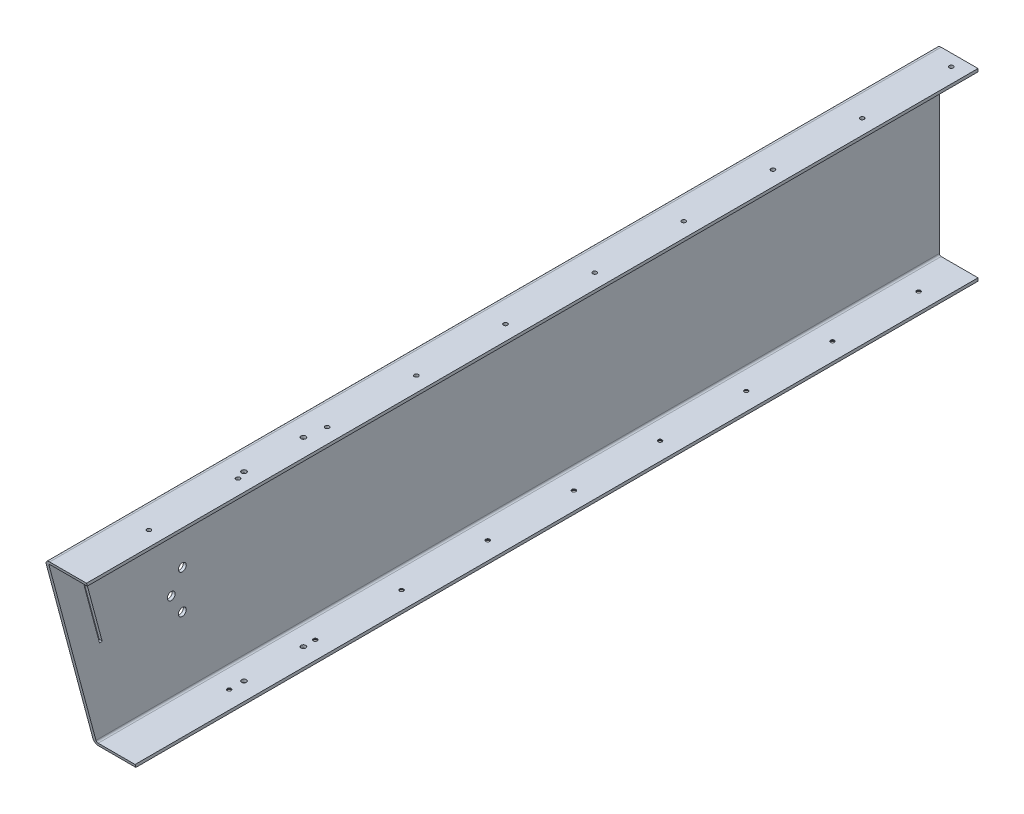
SolidWorks part; units mm, degrees
material "AISI 304"
ref_plane "Спереди" through (0, 0, 0) normal (0, 0, 1) x (1, 0, 0)
ref_plane "Сверху" through (0, 0, 0) normal (0, 1, 0) x (1, 0, 0)
ref_plane "Справа" through (0, 0, 0) normal (1, 0, 0) x (0, 0, -1)
sketch "Эскиз1" plane through (0, 0, 0) normal (0, 0, 1) x (1, 0, 0)
  line L0 (70, -155) -> (8, -155)
  line L1 (0, -147) -> (0, 147)
  line L2 (8, 155) -> (70, 155)
  line L8 (70, -150) -> (8, -150)
  line L9 (5, -147) -> (5, 147)
  line L10 (8, 150) -> (70, 150)
  line L11 (70, 155) -> (70, 150)
  line L12 (70, -150) -> (70, -155)
  arc A0 (0, 147) -> (8, 155) centre (8, 147) cw
  arc A1 (8, -155) -> (0, -147) centre (8, -147) cw
  arc A2 (8, -150) -> (5, -147) centre (8, -147) cw
  arc A3 (5, 147) -> (8, 150) centre (8, 147) cw
  dimension "D2" = 8
  dimension "D3" = 310
  dimension "D1" = 70
  dimension "D4" = 5
extrude "Бобышка-Вытянуть1" add sketch "Эскиз1" along normal blind 1500
sketch "Эскиз2" plane through (0, 0, 0) normal (-1, 0, 0) x (0, 0, 1)
  line L0 (1500, 155) -> (1416.9358, -155)
  line L1 (1500, -155) -> (0, -155) construction
  line L2 (1416.9358, -155) -> (1500, -155)
  line L3 (1500, -155) -> (1500, 155)
  line L4 (1500, 155) -> (0, 155) construction
  dimension "D1" = 75
extrude "Скос" cut sketch "Эскиз2" against normal through all
sketch "Эскиз4" plane through (5, 0, 0) normal (1, 0, 0) x (0, 0, -1)
  line L0 (0, 0) -> (-1255, 0) construction
  line L2 (-1500, 155) -> (-1500, 0) construction
  circle A0 centre (-1255, 0) radius 37.5 construction
  circle A1 centre (-1292.5, 0) radius 6.6
  circle A2 centre (-1273.75, 32.476) radius 6.6
  circle A3 centre (-1236.25, 32.476) radius 6.6 construction
  circle A4 centre (-1217.5, 0) radius 6.6 construction
  circle A5 centre (-1236.25, -32.476) radius 6.6 construction
  circle A6 centre (-1273.75, -32.476) radius 6.6
  point P18 (-1255, 0)
  dimension "D1" = 75
  dimension "D3" = 13.2
  dimension "D4" = 245
  dimension "D2" = 6
extrude "ОТверстия крепления направляющей" cut sketch "Эскиз4" against normal through all
sketch "Эскиз5" plane through (0, -155, 0) normal (0, -1, 0) x (-1, 0, 0)
  line L0 (-40, 0) -> (-40, -1416.9358) construction
  line L1 (-8, 0) -> (-70, 0) construction
  line L2 (-70, -1416.9358) -> (-70, 0) construction
  line L3 (-70, -1416.9358) -> (-8, -1416.9358) construction
  line L5 (-70, -1416.9358) -> (-8, -1416.9358) construction
  point P15 (-40, -1229.9358)
  dimension "D2" = 187
  dimension "D1" = 30
hole_wizard "Зенковка для винта с потайной головкой и внутренним шестигранником M61" positions "Эскиз6" profile "Эскиз7" countersink size "M6" standard "DIN"
sketch "Эскиз6" plane through (0, -155, 0) normal (0, -1, 0) x (-1, 0, 0)
  point P46 (-40, -1229.9358)
sketch "Эскиз7" plane through (40, -155, 1229.9358) normal (1, 0, 0) x (0, 0, -1)
  line L0 (0, 0) -> (0, 31.9828)
  line L1 (0, 31.9828) -> (3.3, 30)
  line L2 (3.3, 30) -> (3.3, 3.555)
  line L3 (3.3, 3.555) -> (6.855, 0)
  line L5 (6.855, 0) -> (0, 0)
  line L6 (-3.3, 3.555) -> (-6.855, 0) construction
  line L10 (0, 31.9828) -> (-3.3, 30) construction
  line L11 (0, -6.35) -> (0, 107.95) construction
  dimension "Диаметр отверстия" = 6.6
  dimension "Глубина отверстия" = 30
  dimension "Диаметр передней зенковки" = 13.71
  dimension "Угол передней зенковки" = 90
  dimension "Угол заточки сверла" = 118
sketch "Эскиз8" plane through (0, -155, 0) normal (0, -1, 0) x (-1, 0, 0)
  line L0 (-70, -1416.9358) -> (-8, -1416.9358) construction
  line L1 (-70, -1416.9358) -> (-70, 0) construction
  line L3 (-8, 152) -> (-70, 152) construction
  circle A0 centre (-35, 305.0642) radius 8.25
  dimension "D1" = 1722
  dimension "D2" = 16.5
  dimension "D4" = 153.0642
  dimension "D3" = 35
extrude "Отверстие для шпильки натяжителя" [suppressed] cut sketch "Эскиз8" against normal blind 10
sketch "Эскиз16" plane through (0, 0, 0) normal (-1, 0, 0) x (0, 0, 1)
  line L8 (1408.9624, -7.2198) -> (1412.8261, -8.2551) construction
  line L9 (1412.8261, -8.2551) -> (1438.708, 88.3375) construction
  line L10 (1438.708, 88.3375) -> (1434.8443, 89.3728) construction
  line L11 (1434.8443, 89.3728) -> (1408.9624, -7.2198) construction
  line L12 (1434.7029, 89.6177) -> (1408.7174, -7.3612)
  line L13 (1408.7174, -7.3612) -> (1412.9675, -8.5)
  line L14 (1412.9675, -8.5) -> (1438.953, 88.4789)
  line L15 (1438.953, 88.4789) -> (1434.7029, 89.6177)
  line L16 (1497.8564, 147) -> (1419.0793, -147) construction
  line L17 (1500, 155) -> (0, 155) construction
  dimension "D2" = 41.75
  dimension "D3" = 100.4
  dimension "D4" = 4.2501
  dimension "D5" = 65.3823
  dimension "D1" = 0.2
extrude "Вырез для пола" cut sketch "Эскиз16" against normal through all both and the other way through all
sketch "Эскиз19" plane through (0, 155, 0) normal (0, 1, 0) x (1, 0, 0)
  line L1 (70, -1500) -> (70, 0) construction
  line L2 (70, -1500) -> (8, -1500) construction
  circle A0 centre (40, -1205) radius 4
  circle A1 centre (40, -1105) radius 4
  dimension "D1" = 8
  dimension "D2" = 295
  dimension "D3" = 30
  dimension "D4" = 2
  dimension "D5" = 100
extrude "Вырез-Вытянуть6" cut sketch "Эскиз19" against normal through all both and the other way through all
pattern_linear "Линейный массив1" count 9 spacing 145 along (0, 0, -1) of "Зенковка для винта с потайной головкой и внутренним шестигранником M61"
sketch "Эскиз25" plane through (0, 155, 0) normal (0, 1, 0) x (1, 0, 0)
  line L0 (70, -1500) -> (70, 0) construction
  line L1 (70, -1500) -> (8, -1500) construction
  point P0 (45, -1370)
  dimension "D1" = 25
  dimension "D2" = 130
hole_wizard "Отверстие обработанное метчиком M82" positions "Эскиз25" profile "Эскиз26" tap size "M8" standard "DIN"
sketch "Эскиз26" plane through (45, 155, 1370) normal (1, 0, 0) x (0, 0, 1)
  line L0 (0, 0) -> (0, 24.2929)
  line L1 (0, 24.2929) -> (3.4, 22.25)
  line L2 (3.4, 22.25) -> (3.4, 0)
  line L5 (3.4, 0) -> (0, 0)
  line L10 (0, 24.2929) -> (-3.4, 22.25) construction
  line L11 (0, -6.35) -> (0, 107.95) construction
  dimension "Диаметр сверла" = 6.8
  dimension "Глубина сверла" = 22.25
  dimension "Угол заточки сверла" = 118
cosmetic thread "Отверстие резьбы28" parameters "D1"=16, "D2"=8
pattern_linear "Линейный массив2" count 10 spacing 150 along (0, 0, -1) of "Отверстие обработанное метчиком M82"
cosmetic thread "Отверстие резьбы29" parameters "D1"=16, "D2"=8
cosmetic thread "Отверстие резьбы30" parameters "D1"=16, "D2"=8
cosmetic thread "Отверстие резьбы31" parameters "D1"=16, "D2"=8
cosmetic thread "Отверстие резьбы32" parameters "D1"=16, "D2"=8
cosmetic thread "Отверстие резьбы33" parameters "D1"=16, "D2"=8
cosmetic thread "Отверстие резьбы34" parameters "D1"=16, "D2"=8
cosmetic thread "Отверстие резьбы35" parameters "D1"=16, "D2"=8
cosmetic thread "Отверстие резьбы36" parameters "D1"=16, "D2"=8
cosmetic thread "Отверстие резьбы37" parameters "D1"=16, "D2"=8
sketch "Эскиз27" plane through (0, 155, 0) normal (0, 1, 0) x (1, 0, 0)
  line L0 (70, -1500) -> (70, 0) construction
  line L2 (70, -1500) -> (8, -1500) construction
  line L3 (70, 0) -> (8, 0) construction
  circle A0 centre (35, 185.5) radius 4.1
  dimension "D1" = 8.2
  dimension "D2" = 35
  dimension "D3" = 1685.5
  dimension "D4" = 185.5
extrude "Отверстие крепления крышки" [suppressed] cut sketch "Эскиз27" against normal blind 10
